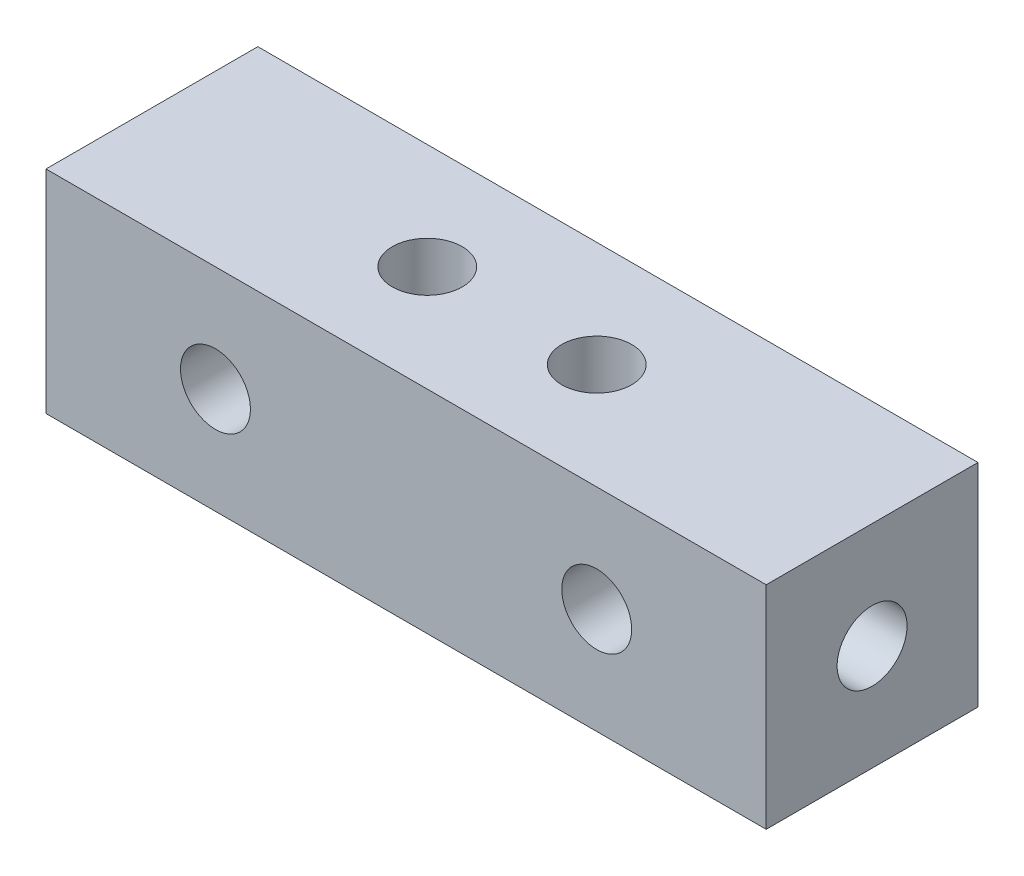
SolidWorks part; units mm, degrees
material "6061 合金"
ref_plane "前视基准面" through (0, 0, 0) normal (0, 0, 1) x (1, 0, 0)
ref_plane "上视基准面" through (0, 0, 0) normal (0, 1, 0) x (1, 0, 0)
ref_plane "右视基准面" through (0, 0, 0) normal (1, 0, 0) x (0, 0, -1)
sketch "草图1" plane through (0, 0, 0) normal (0, 0, 1) x (1, 0, 0)
  line L1 (17, -5) -> (-17, -5)
  line L2 (17, -5) -> (17, 5)
  line L3 (17, 5) -> (-17, 5)
  line L4 (-17, -5) -> (-17, 5)
  line L5 (17, -5) -> (-17, 5) construction
  line L6 (17, 5) -> (-17, -5) construction
  point P0 (0, 0)
  dimension "D1" = 34
  dimension "D2" = 10
extrude "凸台-拉伸1" add sketch "草图1" along normal blind 10
sketch "草图2" plane through (17, 0, 0) normal (1, 0, 0) x (0, 0, -1)
  line L0 (-10, 5) -> (0, -5) construction
  line L1 (0, 5) -> (-10, -5) construction
  line L2 (-10, -5) -> (-10.0774, -5.0758) construction
  point P8 (-5, 0)
sketch "草图3" plane through (0, 5, 0) normal (0, 1, 0) x (1, 0, 0)
  line L0 (17, -10) -> (17, 0) construction
  line L1 (-17, -10) -> (-17, 0) construction
  point P0 (4, -5)
  point P1 (-4, -5)
  dimension "D1" = 13
  dimension "D2" = 13
sketch "草图4" plane through (0, 0, 0) normal (0, 0, -1) x (-1, 0, 0)
  line L0 (-17, -5) -> (-17, 5) construction
  line L1 (17, 5) -> (17, -5) construction
  point P0 (-9, 0)
  point P1 (9, 0)
  dimension "D1" = 8
  dimension "D2" = 8
hole_wizard "M4 螺纹孔的螺纹孔钻头1" positions "3D草图1" profile "草图5" hole size "M4" standard "DIN" end condition through all
sketch3d "3D草图1"
  point P0 (17, 0, 5)
sketch "草图5" plane through (17, 0, 5) normal (0, 1, 0) x (0, 0, -1)
  line L0 (0, 0) -> (0, 34)
  line L1 (0, 34) -> (1.65, 34)
  line L2 (1.65, 34) -> (1.65, 0)
  line L5 (1.65, 0) -> (0, 0)
  line L11 (0, -6.35) -> (0, 107.95) construction
  dimension "通孔孔直径" = 3.3
  dimension "通孔孔深度" = 34
hole_wizard "M4 螺纹孔的螺纹孔钻头2" positions "3D草图2" profile "草图6" hole size "M4" standard "DIN" end condition through all
sketch3d "3D草图2"
  point P0 (4, 5, 5)
sketch "草图6" plane through (4, 5, 5) normal (1, 0, 0) x (0, 0, 1)
  line L0 (0, 0) -> (0, 10)
  line L1 (0, 10) -> (1.65, 10)
  line L2 (1.65, 10) -> (1.65, 0)
  line L5 (1.65, 0) -> (0, 0)
  line L11 (0, -6.35) -> (0, 107.95) construction
  dimension "通孔孔直径" = 3.3
  dimension "通孔孔深度" = 10
hole_wizard "M4 螺纹孔的螺纹孔钻头3" positions "3D草图3" profile "草图7" hole size "M4" standard "DIN" end condition through all
sketch3d "3D草图3"
  point P0 (-4, 5, 5)
sketch "草图7" plane through (-4, 5, 5) normal (1, 0, 0) x (0, 0, 1)
  line L0 (0, 0) -> (0, 10)
  line L1 (0, 10) -> (1.65, 10)
  line L2 (1.65, 10) -> (1.65, 0)
  line L5 (1.65, 0) -> (0, 0)
  line L11 (0, -6.35) -> (0, 107.95) construction
  dimension "通孔孔直径" = 3.3
  dimension "通孔孔深度" = 10
hole_wizard "M4 螺纹孔的螺纹孔钻头4" positions "3D草图4" profile "草图8" hole size "M4" standard "DIN" end condition through all
sketch3d "3D草图4"
  point P0 (9, 0, 0)
sketch "草图8" plane through (9, 0, 0) normal (1, 0, 0) x (0, 1, 0)
  line L0 (0, 0) -> (0, 10)
  line L1 (0, 10) -> (1.65, 10)
  line L2 (1.65, 10) -> (1.65, 0)
  line L5 (1.65, 0) -> (0, 0)
  line L11 (0, -6.35) -> (0, 107.95) construction
  dimension "通孔孔直径" = 3.3
  dimension "通孔孔深度" = 10
hole_wizard "M4 螺纹孔的螺纹孔钻头5" positions "3D草图5" profile "草图9" hole size "M4" standard "DIN" end condition through all
sketch3d "3D草图5"
  point P0 (-9, 0, 0)
sketch "草图9" plane through (-9, 0, 0) normal (1, 0, 0) x (0, 1, 0)
  line L0 (0, 0) -> (0, 10)
  line L1 (0, 10) -> (1.65, 10)
  line L2 (1.65, 10) -> (1.65, 0)
  line L5 (1.65, 0) -> (0, 0)
  line L11 (0, -6.35) -> (0, 107.95) construction
  dimension "通孔孔直径" = 3.3
  dimension "通孔孔深度" = 10
